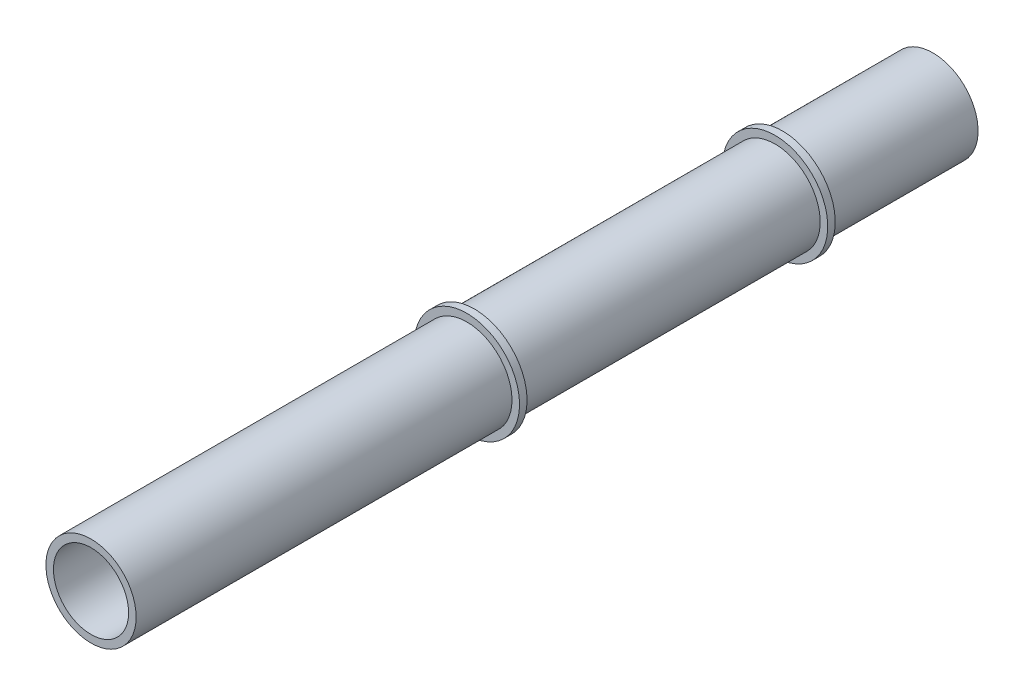
SolidWorks part; units mm, degrees
material "AISI Type 316L stainless steel"
ref_plane "Front Plane" through (0, 0, 0) normal (0, 0, 1) x (1, 0, 0)
ref_plane "Top Plane" through (0, 0, 0) normal (0, 1, 0) x (1, 0, 0)
ref_plane "Right Plane" through (0, 0, 0) normal (1, 0, 0) x (0, 0, -1)
sketch "Sketch1" plane through (0, 0, 0) normal (0, 0, 1) x (1, 0, 0)
  circle A0 centre (0, 0) radius 6
extrude "Boss-Extrude1" add sketch "Sketch1" along normal blind 50
sketch "Sketch2" plane through (0, 0, 0) normal (0, 0, -1) x (-1, 0, 0)
  circle A0 centre (0, 0) radius 7
extrude "Boss-Extrude2" add sketch "Sketch2" along normal blind 1 separate body
sketch "Sketch3" plane through (0, 0, -1) normal (0, 0, -1) x (-1, 0, 0)
  circle A0 centre (0, 0) radius 6
extrude "Boss-Extrude3" add sketch "Sketch3" along normal blind 40 separate body
sketch "Sketch4" plane through (0, 0, -41) normal (0, 0, -1) x (-1, 0, 0)
  circle A0 centre (0, 0) radius 7
extrude "Boss-Extrude4" add sketch "Sketch4" along normal blind 1
sketch "Sketch5" plane through (0, 0, -42) normal (0, 0, -1) x (-1, 0, 0)
  circle A0 centre (0, 0) radius 6
extrude "Boss-Extrude5" add sketch "Sketch5" along normal blind 20
sketch "Sketch6" plane through (0, 0, -62) normal (0, 0, -1) x (-1, 0, 0)
  circle A0 centre (0, 0) radius 5
extrude "Cut-Extrude1" cut sketch "Sketch6" against normal blind 200
